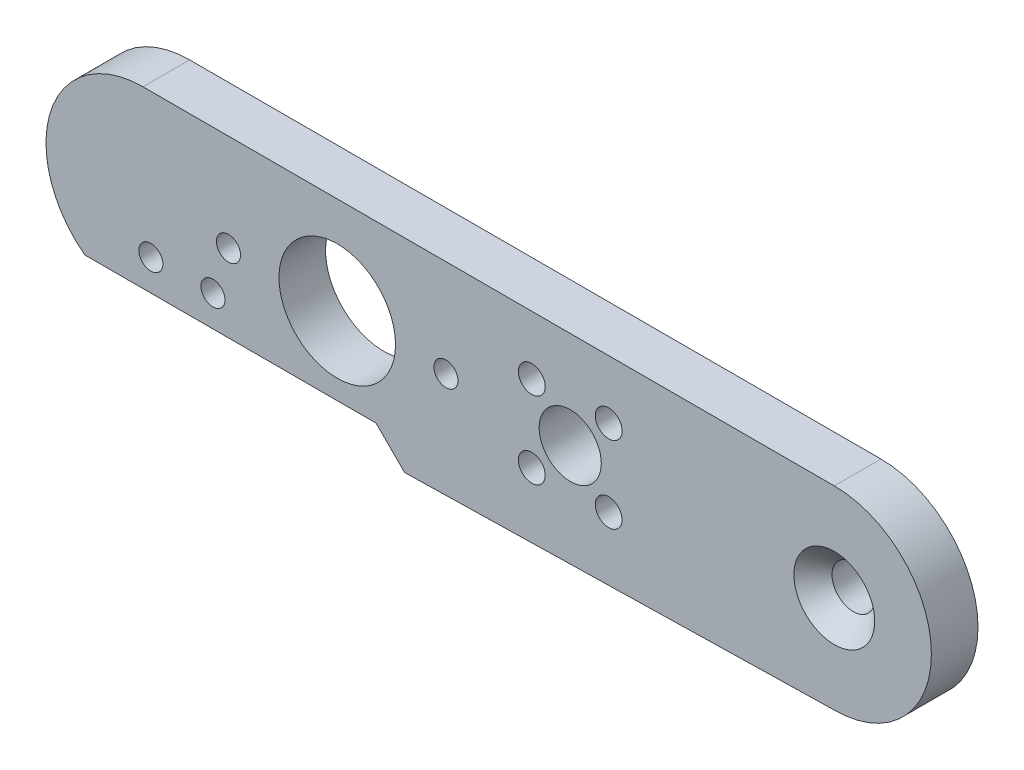
SolidWorks part; units mm, degrees
ref_plane "Front Plane" through (0, 0, 0) normal (0, 0, 1) x (1, 0, 0)
ref_plane "Top Plane" through (0, 0, 0) normal (0, 1, 0) x (1, 0, 0)
ref_plane "Right Plane" through (0, 0, 0) normal (1, 0, 0) x (0, 0, -1)
sketch "Sketch1" plane through (0, 0, 0) normal (0, 0, 1) x (1, 0, 0)
  line L0 (-44.5, 0) -> (44.5, 0) construction
  line L1 (-44.5, 12.5) -> (44.5, 12.5)
  line L2 (-10.8295, -13.6705) -> (44.5, -12.5)
  line L3 (10.5, 0) -> (10.5, 7) construction
  line L4 (10.5, 0) -> (10.5, 7) construction
  line L5 (10.5, 0) -> (15.4497, 4.9497) construction
  line L6 (10.5, 0) -> (14.5, 0) construction
  line L7 (10.5, 0) -> (12.1969, 0) construction
  line L8 (-52, -10) -> (-14.5, -10)
  line L9 (-14.5, -10) -> (-10.8295, -13.6705)
  arc A0 (-44.5, 12.5) -> (-52, -10) centre (-44.5, 0) ccw
  arc A1 (44.5, -12.5) -> (44.5, 12.5) centre (44.5, 0) ccw
  circle A2 centre (10.5, 0) radius 4
  circle A3 centre (10.5, 0) radius 7 construction
  circle A4 centre (15.4497, 4.9497) radius 1.7264
  circle A5 centre (5.5503, 4.9497) radius 1.7264
  circle A6 centre (5.5503, -4.9497) radius 1.7264
  circle A7 centre (15.4497, -4.9497) radius 1.7264
  circle A8 centre (-19.5, 0) radius 7.5
  circle A9 centre (-5.5, 0) radius 1.55
  circle A10 centre (-33.5, 0) radius 1.55
  point P2 (0, 0)
  dimension "D2" = 12.5
  dimension "D3" = 8
  dimension "D5" = 14
  dimension "D7" = 3.4529
  dimension "D11" = 15
  dimension "D12" = 3.1
  dimension "D13" = 3.1
  dimension "D1" = 89
  dimension "D4" = 34
  dimension "D6" = 45
  dimension "D8" = 45
  dimension "D9" = 59
  dimension "D10" = 22.5
  dimension "D14" = 30
  dimension "D15" = 14
  dimension "D16" = 14
extrude "Boss-Extrude1" add sketch "Sketch1" along normal blind 6
hole_wizard "CSK for M5 Flat Head Machine Screw1" positions "Sketch2" profile "Sketch3" countersink size "M5" standard "ANSI Metric" end condition through all
sketch "Sketch2" plane through (0, 0, 6) normal (0, 0, 1) x (1, 0, 0)
  point P0 (44.5, 0)
  point P3 (44.5, 0)
sketch "Sketch3" plane through (44.5, 0, 6) normal (1, 0, 0) x (0, -1, 0)
  line L0 (0, 0) -> (0, 6)
  line L1 (0, 6) -> (2.925, 6)
  line L2 (2.75, 5.825) -> (2.75, 2.45)
  line L3 (2.75, 2.45) -> (5.2, 0)
  line L5 (5.2, 0) -> (0, 0)
  line L6 (-2.75, 2.45) -> (-5.2, 0) construction
  line L7 (2.925, 6) -> (2.75, 5.825)
  line L8 (-2.925, 6) -> (-2.75, 5.825) construction
  line L11 (0, -6.35) -> (0, 107.95) construction
  dimension "Thru Hole Dia." = 5.5
  dimension "Thru Hole Depth" = 6
  dimension "Near C'Sink Dia." = 10.4
  dimension "Near C'Sink Angle" = 90
  dimension "Far C'Sink Dia." = 5.85
  dimension "Far C'Sink Angle" = 90
sketch "Sketch4" plane through (0, 0, 6) normal (0, 0, 1) x (1, 0, 0)
  line L0 (-48.4812, -6) -> (-30.1661, -6) construction
  line L1 (44.5, 12.5) -> (-44.5, 12.5) construction
  circle A0 centre (-43.5, -6) radius 1.55
  circle A1 centre (-35.5, -6) radius 1.55
  circle A2 centre (-19.5, 0) radius 7.5 construction
  dimension "D2" = 3.1
  dimension "D3" = 3.1
  dimension "D4" = 16
  dimension "D1" = 18.5
  dimension "D5" = 8
extrude "Cut-Extrude1" cut sketch "Sketch4" against normal blind 3
sketch "Sketch5" plane through (0, 0, 3) normal (0, 0, 1) x (1, 0, 0)
  circle A0 centre (-35.5, -6) radius 3
  circle A1 centre (-43.5, -6) radius 3
extrude "Cut-Extrude2" cut sketch "Sketch5" against normal through all
